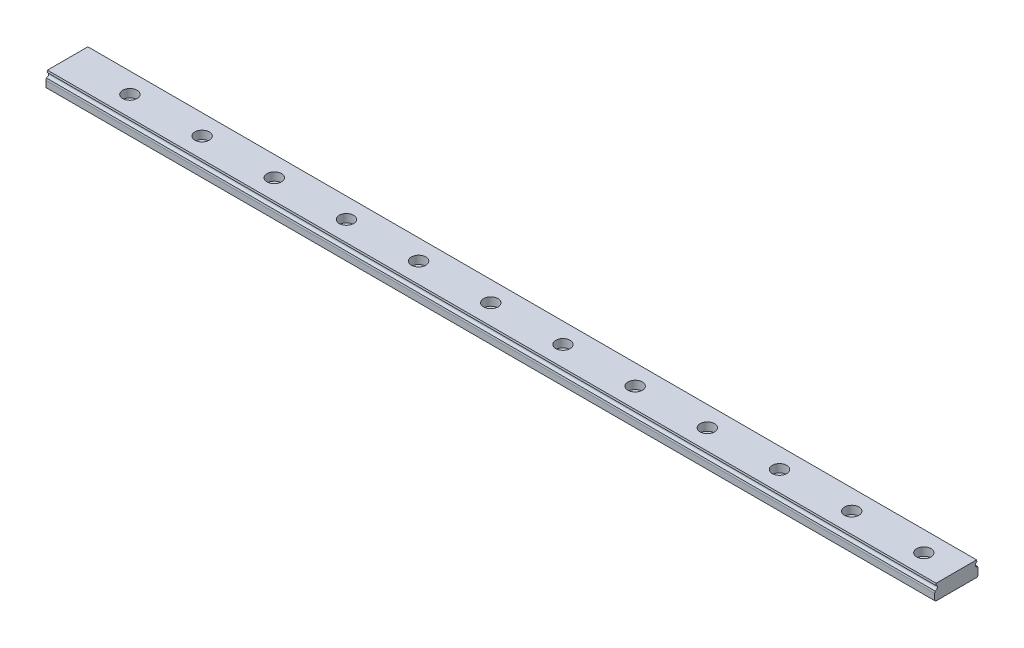
SolidWorks part; units mm, degrees
ref_plane "Plano frontal" through (0, 0, 0) normal (0, 0, 1) x (1, 0, 0)
ref_plane "Plano superior" through (0, 0, 0) normal (0, 1, 0) x (1, 0, 0)
ref_plane "Plano direito" through (0, 0, 0) normal (1, 0, 0) x (0, 0, -1)
ref_plane "Plano1" through (-15, 0, 0) normal (1, 0, 0) x (0, 0, -1)
sketch "Esboço1" plane through (-15, 0, 0) normal (1, 0, 0) x (0, 0, -1)
  line L0 (-12, 4) -> (-12, 0.5)
  line L1 (-12, 0.5) -> (-11.5, 0)
  line L2 (-11.5, 0) -> (11.5, 0)
  line L3 (11.5, 0) -> (12, 0.5)
  line L4 (12, 0.5) -> (12, 4)
  line L5 (12, 4) -> (11.8146, 5.0517)
  line L6 (11.3837, 7.4951) -> (11.2065, 8.5)
  line L7 (11.2065, 8.5) -> (-11.2065, 8.5)
  line L8 (-11.2065, 8.5) -> (-11.3837, 7.4951)
  line L9 (-11.8146, 5.0517) -> (-12, 4)
  arc A0 (11.8146, 5.0517) -> (11.3837, 7.4951) centre (11.75, 6.3) cw
  arc A1 (-11.3837, 7.4951) -> (-11.8146, 5.0517) centre (-11.75, 6.3) cw
extrude "Ressalto-extrusão1" add sketch "Esboço1" along normal blind 353 and the other way blind 139.5
ref_plane "Plano2" through (0, 0, 0) normal (0, 0, 1) x (1, 0, 0)
sketch "Esboço2" plane through (0, 0, 0) normal (0, 0, 1) x (1, 0, 0)
  line L0 (0, 8.5) -> (4, 8.5)
  line L1 (4, 8.5) -> (4, 4)
  line L2 (4, 4) -> (2.25, 4)
  line L3 (2.25, 4) -> (2.25, 0)
  line L4 (2.25, 0) -> (0, 0)
  line L5 (0, 0) -> (0, 8.5)
  line L6 (0, 0) -> (0, 8.5) construction
ref_plane "Plano3" through (0, 0, 0) normal (0, 0, 1) x (1, 0, 0)
sketch "Esboço3" plane through (0, 0, 0) normal (0, 0, 1) x (1, 0, 0)
  line L0 (40, 8.5) -> (44, 8.5)
  line L1 (44, 8.5) -> (44, 4)
  line L2 (44, 4) -> (42.25, 4)
  line L3 (42.25, 4) -> (42.25, 0)
  line L4 (42.25, 0) -> (40, 0)
  line L5 (40, 0) -> (40, 8.5)
  line L6 (40, 0) -> (40, 8.5) construction
revolve "Corte-Revolução2" cut sketch "Esboço3" angle 360 about L6
pattern_linear "LPattern1" count 8 spacing 40 along (1, 0, 0) count 5 spacing 40 along (-1, 0, 0) of "Corte-Revolução2"
